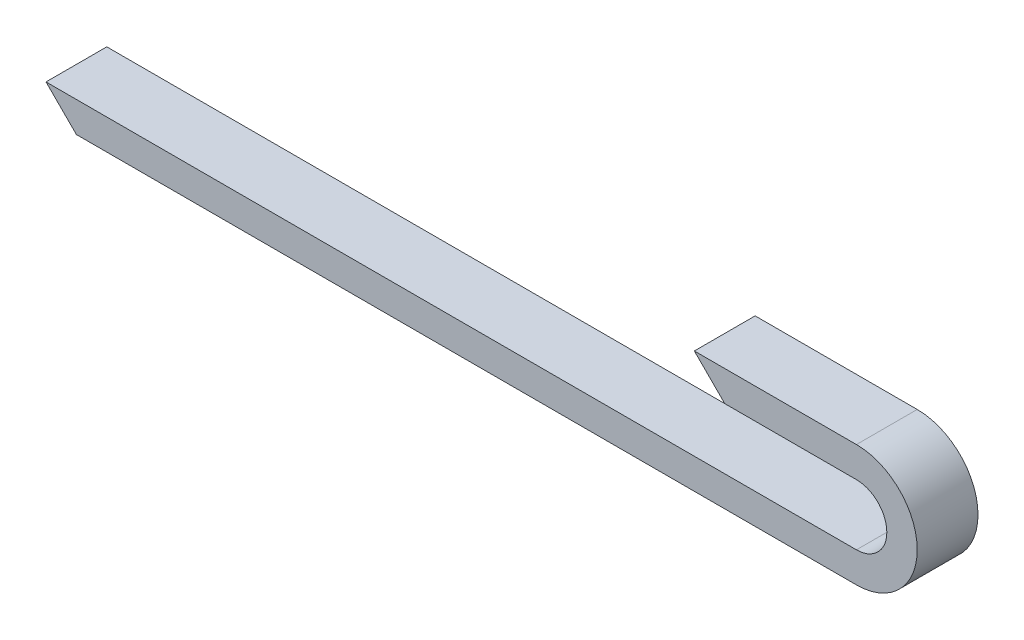
SolidWorks part; units mm, degrees
ref_plane "前视基准面" through (0, 0, 0) normal (0, 0, 1) x (1, 0, 0)
ref_plane "上视基准面" through (0, 0, 0) normal (0, 1, 0) x (1, 0, 0)
ref_plane "右视基准面" through (0, 0, 0) normal (1, 0, 0) x (0, 0, -1)
sketch "草图1" plane through (0, 0, 0) normal (0, 0, 1) x (1, 0, 0)
  line L0 (111.3001, 44.9564) -> (126.3001, 29.9564)
  line L1 (-208.6999, -0.0436) -> (191.3001, -0.0436)
  line L5 (191.3001, 44.9564) -> (111.3001, 44.9564)
  line L6 (191.3001, 29.9564) -> (126.3001, 29.9564)
  line L7 (191.3001, -15.0436) -> (-193.6999, -15.0436)
  line L8 (-193.6999, -15.0436) -> (-208.6999, -0.0436)
  arc A2 (191.3001, 29.9564) -> (191.3001, -0.0436) centre (191.3001, 14.9564) cw
  arc A3 (191.3001, 44.9564) -> (191.3001, -15.0436) centre (191.3001, 14.9564) cw
  point P9 (191.3001, 29.9564)
  dimension "D2" = 400
extrude "凸台-拉伸1" add sketch "草图1" against normal blind 30
scale "缩放比例1" scale about origin uniform scaling yes scale factor 1.7
